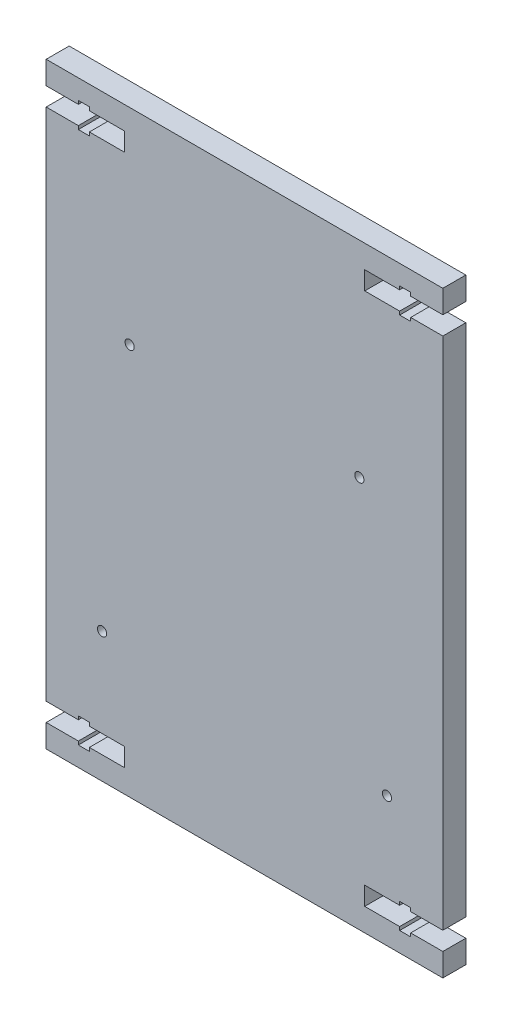
SolidWorks part; units mm, degrees
ref_plane "Front Plane" through (0, 0, 0) normal (0, 0, 1) x (1, 0, 0)
ref_plane "Top Plane" through (0, 0, 0) normal (0, 1, 0) x (1, 0, 0)
ref_plane "Right Plane" through (0, 0, 0) normal (1, 0, 0) x (0, 0, -1)
sketch "Sketch1" plane through (0, 0, 0) normal (0, 0, 1) x (1, 0, 0)
  line L1 (-34.0876, 102.9521) -> (52.2389, 102.9521)
  line L2 (-34.0876, 102.9521) -> (-34.0876, -27.0479)
  line L3 (-34.0876, -27.0479) -> (52.2389, -27.0479)
  line L4 (52.2389, 102.9521) -> (52.2389, -27.0479)
  dimension "D1" = 130
extrude "Boss-Extrude1" add sketch "Sketch1" along normal blind 5
sketch "Sketch3" plane through (0, 0, 5) normal (0, 0, 1) x (1, 0, 0)
  line L0 (-34.0876, -18.0479) -> (-27.0876, -18.0479)
  line L1 (-34.0876, 102.9521) -> (-34.0876, -27.0479) construction
  line L2 (-17.0876, -18.0479) -> (-17.0876, -22.0479)
  line L3 (-17.0876, -22.0479) -> (-24.6876, -22.0479)
  line L4 (-34.0876, -27.0479) -> (52.2389, -27.0479) construction
  line L5 (-27.0876, -18.0479) -> (-27.0876, -17.2979)
  line L6 (-27.0876, -17.2979) -> (-24.6876, -17.2979)
  line L7 (-24.6876, -17.2979) -> (-24.6876, -18.0479)
  line L8 (-24.6876, -22.0479) -> (-24.6876, -22.7979)
  line L9 (-24.6876, -22.7979) -> (-27.0876, -22.7979)
  line L10 (-27.0876, -22.7979) -> (-27.0876, -22.0479)
  line L11 (-34.0876, 37.9521) -> (52.2389, 37.9521) construction
  line L12 (52.2389, -27.0479) -> (52.2389, 102.9521) construction
  line L13 (9.0757, 102.9521) -> (9.0757, -27.0479) construction
  line L14 (52.2389, 102.9521) -> (-34.0876, 102.9521) construction
  line L15 (-24.6876, -18.0479) -> (-17.0876, -18.0479)
  line L16 (-27.0876, -22.0479) -> (-34.0876, -22.0479)
  line L17 (-34.0876, -18.0479) -> (-34.0876, -22.0479)
  line L18 (52.2389, -18.0479) -> (52.2389, -22.0479)
  line L19 (45.2389, -22.0479) -> (52.2389, -22.0479)
  line L20 (42.8389, -18.0479) -> (35.2389, -18.0479)
  line L21 (45.2389, -22.7979) -> (45.2389, -22.0479)
  line L22 (42.8389, -22.7979) -> (45.2389, -22.7979)
  line L23 (42.8389, -22.0479) -> (42.8389, -22.7979)
  line L24 (42.8389, -17.2979) -> (42.8389, -18.0479)
  line L25 (45.2389, -17.2979) -> (42.8389, -17.2979)
  line L26 (45.2389, -18.0479) -> (45.2389, -17.2979)
  line L27 (35.2389, -22.0479) -> (42.8389, -22.0479)
  line L28 (35.2389, -18.0479) -> (35.2389, -22.0479)
  line L29 (52.2389, -18.0479) -> (45.2389, -18.0479)
  line L30 (52.2389, 93.9521) -> (45.2389, 93.9521)
  line L31 (35.2389, 93.9521) -> (35.2389, 97.9521)
  line L32 (35.2389, 97.9521) -> (42.8389, 97.9521)
  line L33 (45.2389, 93.9521) -> (45.2389, 93.2021)
  line L34 (45.2389, 93.2021) -> (42.8389, 93.2021)
  line L35 (42.8389, 93.2021) -> (42.8389, 93.9521)
  line L36 (42.8389, 97.9521) -> (42.8389, 98.7021)
  line L37 (42.8389, 98.7021) -> (45.2389, 98.7021)
  line L38 (45.2389, 98.7021) -> (45.2389, 97.9521)
  line L39 (42.8389, 93.9521) -> (35.2389, 93.9521)
  line L40 (45.2389, 97.9521) -> (52.2389, 97.9521)
  line L41 (52.2389, 93.9521) -> (52.2389, 97.9521)
  line L42 (-34.0876, 93.9521) -> (-34.0876, 97.9521)
  line L43 (-27.0876, 97.9521) -> (-34.0876, 97.9521)
  line L44 (-24.6876, 93.9521) -> (-17.0876, 93.9521)
  line L45 (-27.0876, 98.7021) -> (-27.0876, 97.9521)
  line L46 (-24.6876, 98.7021) -> (-27.0876, 98.7021)
  line L47 (-24.6876, 97.9521) -> (-24.6876, 98.7021)
  line L48 (-24.6876, 93.2021) -> (-24.6876, 93.9521)
  line L49 (-27.0876, 93.2021) -> (-24.6876, 93.2021)
  line L50 (-27.0876, 93.9521) -> (-27.0876, 93.2021)
  line L51 (-17.0876, 97.9521) -> (-24.6876, 97.9521)
  line L52 (-17.0876, 93.9521) -> (-17.0876, 97.9521)
  line L53 (-34.0876, 93.9521) -> (-27.0876, 93.9521)
  dimension "D1" = 5
  dimension "D2" = 4
  dimension "D3" = 17
  dimension "D4" = 0.75
  dimension "D5" = 0.75
  dimension "D6" = 2.4
  dimension "D7" = 2.4
  dimension "D8" = 7
extrude "Cut-Extrude2" cut sketch "Sketch3" against normal blind 10
sketch "Sketch4" plane through (0, 0, 5) normal (0, 0, 1) x (1, 0, 0)
  circle A0 centre (40.0757, 1.2329) radius 1 construction
  circle A1 centre (40.0757, 1.2329) radius 1
  circle A2 centre (-21.9243, 1.2329) radius 1 construction
  circle A3 centre (-21.9243, 1.2329) radius 1
  circle A4 centre (-15.9243, 58.2329) radius 1 construction
  circle A5 centre (-15.9243, 58.2329) radius 1
  circle A6 centre (34.0757, 58.2329) radius 1 construction
  circle A7 centre (34.0757, 58.2329) radius 1
extrude "Cut-Extrude3" cut sketch "Sketch4" against normal blind 10
